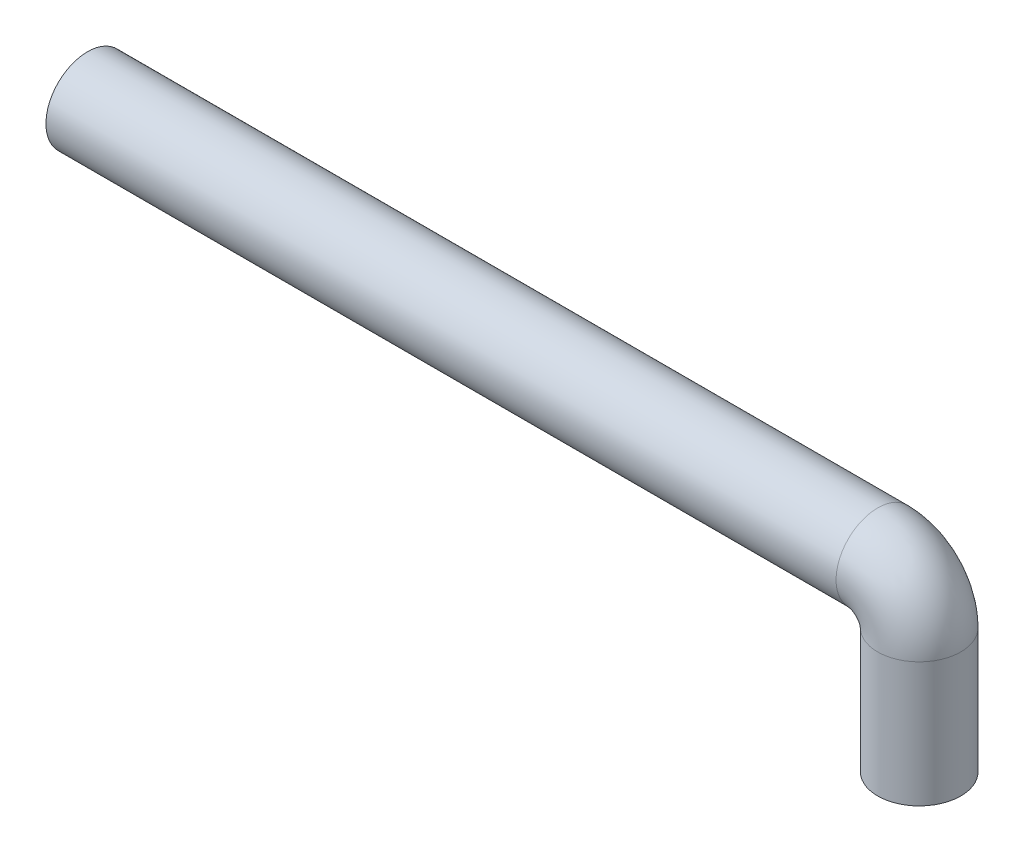
SolidWorks part; units mm, degrees
material "1023 Carbon Steel Sheet (SS)"
ref_plane "Front Plane" through (0, 0, 0) normal (0, 0, 1) x (1, 0, 0)
ref_plane "Top Plane" through (0, 0, 0) normal (0, 1, 0) x (1, 0, 0)
ref_plane "Right Plane" through (0, 0, 0) normal (1, 0, 0) x (0, 0, -1)
sketch "Sketch2" plane through (0, 0, 0) normal (0, 0, 1) x (1, 0, 0)
  line L0 (0, 0) -> (30.1625, 0)
  line L1 (31.75, -1.5875) -> (31.75, -6.35)
  arc A0 (30.1625, 0) -> (31.75, -1.5875) centre (30.1625, -1.5875) cw
  point P6 (31.75, 0)
  dimension "D3" = 1.5875
  dimension "D1" = 6.35
  dimension "D2" = 31.75
sketch "Sketch3" plane through (0, 0, 0) normal (1, 0, 0) x (0, 0, -1)
  circle A0 centre (0, 0) radius 1.5875
  dimension "D1" = 3.175
sweep "Sweep1" add profiles "Sketch3" path "Sketch2"
